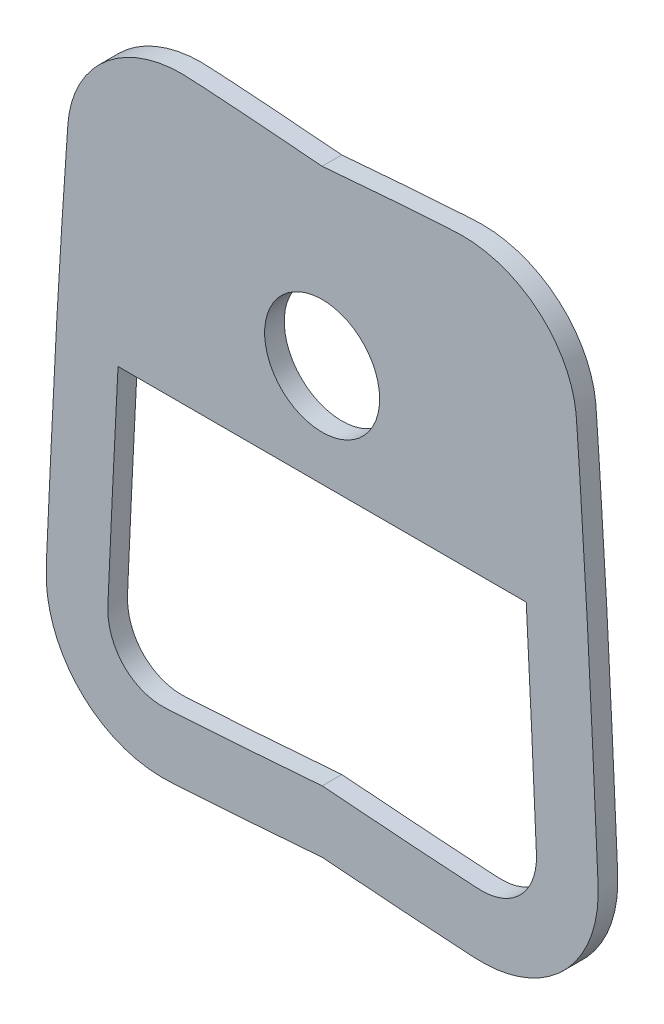
SolidWorks part; units mm, degrees
material "Фанера"
ref_plane "Front Plane" through (0, 0, 0) normal (0, 0, 1) x (1, 0, 0)
ref_plane "Top Plane" through (0, 0, 0) normal (0, 1, 0) x (1, 0, 0)
ref_plane "Right Plane" through (0, 0, 0) normal (1, 0, 0) x (0, 0, -1)
sketch "Эскиз2" plane through (0, 0, 0) normal (0, 0, 1) x (1, 0, 0)
  line L0 (0.0002, 142.4737) -> (0.0002, 32.0804) construction
  line L1 (-29.1091, 89.0073) -> (29.109, 89.0073)
  circle A1 centre (0, 103.6369) radius 4.3081 construction
  circle A2 centre (0, 103.6369) radius 8.2
  spline S2 degree 3 poles (0, 43.7392) (0.774, 43.6784) (2.3219, 43.5569) (5.4182, 43.3194) (9.2893, 43.031) (13.1618, 42.7628) (16.2603, 42.556) (18.2795, 42.4223) (19.829, 42.3235) (20.7864, 42.2641) (21.4427, 42.2247) (21.9494, 42.1945) (22.4153, 42.1814) (22.8397, 42.1798) (23.5161, 42.1932) (24.4211, 42.254) (25.9575, 42.4683) (27.8265, 42.9386) (29.9778, 43.8332) (31.9662, 45.0352) (33.7585, 46.5263) (35.2935, 48.2541) (36.5751, 50.2162) (37.5523, 52.3332) (38.105, 54.2013) (38.3902, 55.7262) (38.4987, 56.6607) (38.551, 57.4525) (38.5708, 58.0629) (38.5684, 58.6713) (38.5362, 59.4435) (38.4938, 60.3708) (38.425, 61.9202) (38.3386, 63.836) (38.1977, 66.9444) (38.0221, 70.7707) (37.7348, 76.9141) (37.3647, 84.5565) (36.9475, 92.2471) (36.583, 98.3866) (36.2979, 102.9638) (35.9998, 107.5529) (35.7664, 111.0027) (35.6046, 113.3302) (35.5424, 114.2245) (35.4966, 114.8654) (35.4694, 115.2725) (35.4118, 115.9083) (35.279, 116.8133) (35.0277, 117.9094) (34.5635, 119.3731) (33.7816, 121.0943) (32.5083, 123.0216) (30.9852, 124.6902) (29.1803, 126.1544) (27.5041, 127.1401) (25.3505, 128.0897) (23.409, 128.6293) (21.5202, 128.866) (20.353, 128.9311) (19.2879, 128.9227) (18.2137, 128.846) (17.2299, 128.7853) (16.3005, 128.7246) (15.3917, 128.6651) (14.5031, 128.6059) (13.1677, 128.5157) (11.3632, 128.3907) (9.078, 128.2256) (6.7985, 128.0531) (4.5827, 127.8775) (2.325, 127.6918) (0.8119, 127.5588) (0, 127.4874) knots 0 0 0 0 0.015767 0.031534 0.063068 0.094601 0.110368 0.126135 0.1357 0.141901 0.145616 0.149053 0.152208 0.155081 0.157671 0.165946 0.173483 0.189156 0.204936 0.220629 0.236165 0.252111 0.267386 0.2836 0.29929 0.306809 0.315089 0.318377 0.322921 0.32749 0.330729 0.338618 0.346341 0.362227 0.377566 0.409533 0.440017 0.50247 0.564923 0.596433 0.627377 0.65806 0.68983 0.697599 0.705443 0.708037 0.710647 0.713729 0.721 0.729205 0.736538 0.752162 0.767416 0.783272 0.797847 0.814472 0.822575 0.845629 0.855017 0.861206 0.869358 0.876627 0.883074 0.889378 0.895542 0.90157 0.907464 0.922725 0.938305 0.953995 0.969152 0.983448 1 1 1 1 construction
  spline S3 degree 3 poles (0, 127.4874) (-0.5484, 127.5359) (-1.5966, 127.6285) (-3.0967, 127.7551) (-4.7859, 127.8937) (-6.7383, 128.0484) (-9.7405, 128.276) (-12.7364, 128.4878) (-15.7405, 128.6886) (-17.4164, 128.7977) (-18.5445, 128.868) (-19.0935, 128.9048) (-19.6713, 128.9252) (-20.3714, 128.9252) (-21.3283, 128.8823) (-22.828, 128.7123) (-24.7405, 128.2795) (-27.1793, 127.3552) (-29.6475, 125.8824) (-31.8744, 123.83) (-33.4877, 121.6318) (-34.5579, 119.4542) (-35.0467, 117.8648) (-35.2691, 116.8043) (-35.3671, 116.2217) (-35.4408, 115.6222) (-35.489, 114.9922) (-35.5347, 114.3247) (-35.5881, 113.5686) (-35.73, 111.5277) (-35.9533, 108.2526) (-36.3451, 102.257) (-36.8092, 94.7185) (-37.2262, 87.1491) (-37.5342, 81.0394) (-37.7522, 76.5283) (-37.9656, 71.9894) (-38.1394, 68.2173) (-38.2787, 65.1601) (-38.363, 63.2949) (-38.43, 61.8051) (-38.4797, 60.6971) (-38.5314, 59.5351) (-38.5811, 58.4168) (-38.5535, 57.4313) (-38.4964, 56.6729) (-38.4026, 55.8505) (-38.2454, 54.9051) (-37.8731, 53.3446) (-37.2011, 51.4698) (-36.0559, 49.337) (-34.6245, 47.4301) (-32.8958, 45.7468) (-30.9374, 44.3573) (-28.7768, 43.2834) (-26.8641, 42.6757) (-25.2893, 42.3656) (-24.1298, 42.2273) (-22.9233, 42.1676) (-21.9573, 42.1912) (-21.168, 42.2417) (-20.6015, 42.2755) (-19.9623, 42.3153) (-19.0057, 42.3758) (-17.9649, 42.4432) (-16.7625, 42.5228) (-15.6619, 42.5959) (-14.1289, 42.6985) (-12.1179, 42.8348) (-8.905, 43.0601) (-5.6195, 43.3041) (-2.4082, 43.5501) (-0.8027, 43.6762) (0, 43.7392) knots 0 0 0 0 0.011181 0.021372 0.030575 0.045603 0.061149 0.091723 0.106599 0.122298 0.125831 0.129556 0.13347 0.137573 0.143772 0.152913 0.168196 0.183457 0.205727 0.226104 0.244563 0.260782 0.275163 0.278191 0.282787 0.287159 0.290453 0.295617 0.300749 0.305846 0.337168 0.36742 0.427874 0.490561 0.521384 0.552117 0.582286 0.613668 0.628808 0.644442 0.651588 0.659095 0.666967 0.675214 0.68182 0.686975 0.690658 0.698628 0.706421 0.72322 0.738904 0.755424 0.771444 0.787719 0.803991 0.820255 0.828308 0.836564 0.843949 0.852824 0.85617 0.860012 0.864349 0.869177 0.879481 0.88553 0.893651 0.901883 0.916735 0.934588 0.967294 0.983647 1 1 1 1 construction
  spline S4 degree 1 poles (0.0001, 51.7639) (-0.0019, 119.4564) knots 0 0 1 1 construction
  spline S5 degree 1 poles (-0.0019, 119.4564) (0.0001, 51.7639) knots 0 0 1 1 construction
  spline S6 degree 3 poles (0.0001, 51.7639) (1.5422, 51.6427) (4.6296, 51.401) (9.243, 51.0555) (13.08, 50.7868) (16.1635, 50.5801) (18.0968, 50.4516) (19.6289, 50.3523) (20.5869, 50.2918) (21.254, 50.2507) (21.6314, 50.2278) (21.9256, 50.2102) (22.1901, 50.1945) (22.3388, 50.1873) (22.487, 50.1828) (22.8167, 50.1783) (23.2689, 50.1916) (24.0642, 50.2695) (25.0003, 50.4673) (26.0799, 50.8663) (27.0688, 51.4124) (27.9574, 52.0949) (28.7407, 52.9108) (29.4014, 53.845) (29.9298, 54.8885) (30.2479, 55.8344) (30.4233, 56.6228) (30.5142, 57.2296) (30.556, 57.7405) (30.5692, 58.1757) (30.5687, 58.4382) (30.5634, 58.6211) (30.5529, 58.8728) (30.5404, 59.1612) (30.5151, 59.7274) (30.4574, 61.0064) (30.3716, 62.9287) (30.2659, 65.2578) (30.1601, 67.5799) (30.0176, 70.6778) (29.7646, 76.0976) (29.4758, 82.0809) (29.2034, 87.2793) (29.0352, 90.363) (28.8501, 93.6446) (28.6103, 97.6967) (28.3225, 102.3235) (28.0723, 106.1791) (27.8916, 108.8771) (27.7868, 110.4188) (27.7074, 111.5742) (27.6403, 112.5392) (27.5865, 113.3126) (27.5533, 113.7866) (27.5256, 114.1729) (27.4961, 114.6058) (27.4793, 114.8088) (27.4496, 115.0557) (27.3943, 115.392) (27.3, 115.8066) (27.0984, 116.4438) (26.7372, 117.2359) (26.1497, 118.1141) (25.1669, 119.176) (23.9141, 120.0231) (22.4672, 120.583) (21.4971, 120.8065) (20.6992, 120.9008) (20.201, 120.9255) (19.78, 120.9237) (19.4766, 120.9129) (19.0179, 120.8838) (18.163, 120.8267) (17.2431, 120.7699) (16.074, 120.6926) (14.9273, 120.6165) (13.3895, 120.5121) (11.4734, 120.3785) (8.414, 120.1552) (5.3428, 119.9155) (2.3164, 119.6612) (0.7679, 119.5241) (-0.0019, 119.4564) knots -0.004253 -0.004253 -0.004253 -0.004253 0.027279 0.058811 0.090343 0.106109 0.121875 0.129759 0.137642 0.141583 0.143554 0.145525 0.147495 0.149466 0.151437 0.153408 0.161291 0.169174 0.18494 0.200706 0.216472 0.232238 0.248004 0.26377 0.279536 0.295302 0.303185 0.311068 0.318951 0.322893 0.326834 0.328805 0.330776 0.332746 0.334717 0.3426 0.358366 0.374132 0.389898 0.405664 0.437196 0.500261 0.527717 0.543483 0.563325 0.594857 0.626389 0.657921 0.673687 0.68157 0.689453 0.697336 0.701278 0.705219 0.70719 0.709161 0.713102 0.717044 0.720985 0.728868 0.736751 0.752517 0.768283 0.784049 0.815582 0.831348 0.847114 0.854997 0.86288 0.866821 0.870763 0.874704 0.878646 0.886529 0.894412 0.902295 0.910178 0.925944 0.94171 0.973242 0.989008 1.004774 1.004774 1.004774 1.004774
  spline S7 degree 3 poles (-0.0019, 119.4564) (-0.7698, 119.5242) (-2.3118, 119.6615) (-5.3473, 119.9152) (-8.4132, 120.1552) (-11.4731, 120.3784) (-13.7726, 120.539) (-15.6942, 120.6678) (-17.0401, 120.7562) (-17.8067, 120.8057) (-18.3769, 120.842) (-18.8623, 120.8721) (-19.2727, 120.899) (-19.4779, 120.9114) (-19.6278, 120.9182) (-19.8368, 120.9244) (-20.1909, 120.9254) (-20.7023, 120.9009) (-21.4955, 120.8063) (-22.4658, 120.5842) (-23.9103, 120.0245) (-25.1675, 119.1756) (-26.1489, 118.1151) (-26.7389, 117.232) (-27.0968, 116.4493) (-27.3022, 115.7974) (-27.3928, 115.4011) (-27.4431, 115.0936) (-27.4659, 114.9214) (-27.4774, 114.8174) (-27.488, 114.6997) (-27.5127, 114.3681) (-27.5453, 113.898) (-27.5871, 113.3007) (-27.6405, 112.539) (-27.7074, 111.5717) (-27.7869, 110.416) (-27.8918, 108.8736) (-28.0726, 106.1765) (-28.3227, 102.3205) (-28.6106, 97.6944) (-28.8501, 93.6433) (-29.0352, 90.362) (-29.2036, 87.2786) (-29.4757, 82.081) (-29.7648, 76.0951) (-30.0177, 70.6763) (-30.1601, 67.5786) (-30.2662, 65.255) (-30.3538, 63.3188) (-30.4235, 61.7694) (-30.4758, 60.6068) (-30.5185, 59.6416) (-30.5539, 58.8626) (-30.5684, 58.4381) (-30.5695, 58.1742) (-30.56, 57.8625) (-30.5387, 57.5326) (-30.499, 57.1267) (-30.4233, 56.6232) (-30.2478, 55.8336) (-29.929, 54.8871) (-29.4012, 53.8441) (-28.7402, 52.9103) (-27.9574, 52.0948) (-27.0665, 51.4111) (-26.0801, 50.8662) (-24.9975, 50.467) (-24.0696, 50.2699) (-23.2587, 50.191) (-22.7849, 50.1771) (-22.324, 50.1876) (-21.9772, 50.2059) (-21.3268, 50.2467) (-20.5986, 50.2907) (-19.6237, 50.3527) (-18.0991, 50.4513) (-16.1627, 50.5802) (-13.0782, 50.7868) (-9.2439, 51.0555) (-4.6291, 51.401) (-1.542, 51.6428) (0.0001, 51.7639) knots -0.004774 -0.004774 -0.004774 -0.004774 0.010992 0.026758 0.05829 0.074056 0.089822 0.105588 0.113471 0.117413 0.121354 0.125296 0.127266 0.129237 0.131208 0.133179 0.13712 0.145003 0.152886 0.168652 0.184418 0.21595 0.231717 0.247483 0.263249 0.271132 0.279015 0.282956 0.284927 0.286898 0.288868 0.290839 0.294781 0.298722 0.302664 0.310547 0.31843 0.326313 0.342079 0.373611 0.405143 0.436675 0.456499 0.472265 0.499739 0.562804 0.594336 0.610102 0.625868 0.641634 0.649517 0.6574 0.665283 0.669224 0.673166 0.677107 0.681049 0.68499 0.688932 0.696815 0.704698 0.720464 0.73623 0.751996 0.767762 0.783528 0.799294 0.81506 0.830826 0.838709 0.846593 0.850534 0.854476 0.858417 0.862359 0.870242 0.878125 0.893891 0.909657 0.941189 0.972721 1.004253 1.004253 1.004253 1.004253
  spline S8 degree 1 poles (0, 42.9368) (0.0002, 128.2905) knots 0 0 1 1 construction
  spline S9 degree 1 poles (0.0002, 128.2905) (0, 42.9368) knots 0 0 1 1 construction
  spline S10 degree 3 poles (0, 42.9368) (3.067, 42.6959) (7.6671, 42.3407) (13.8079, 41.9178) (17.6422, 41.6576) (20.332, 41.4944) (21.8672, 41.3895) (23.4939, 41.3645) (25.4979, 41.5458) (28.6557, 42.2954) (32.3308, 44.0858) (35.9131, 47.4475) (38.3517, 51.6969) (39.2064, 55.2633) (39.3721, 57.6662) (39.3641, 59.2909) (39.2097, 61.9411) (39.0559, 65.8023) (38.8386, 70.4033) (38.6252, 75.0129) (38.4046, 79.6203) (38.0995, 85.7648) (37.6849, 93.4448) (37.2183, 101.1217) (36.8709, 106.4932) (36.6651, 109.5632) (36.5105, 111.8628) (36.3696, 113.7875) (36.2773, 115.308) (36.0967, 116.9449) (35.6112, 118.9138) (34.338, 121.9196) (31.8813, 125.2086) (28.5527, 127.5934) (25.5712, 128.8586) (23.2184, 129.4757) (20.8128, 129.7689) (18.3873, 129.674) (16.1209, 129.512) (13.0387, 129.3125) (9.2066, 129.0403) (4.6006, 128.6872) (1.5335, 128.4253) (0.0002, 128.2905) knots 0.000425 0.000425 0.000425 0.000425 0.062869 0.094091 0.125312 0.140923 0.148729 0.156534 0.172145 0.187756 0.218978 0.2502 0.281421 0.312643 0.320449 0.328254 0.343865 0.375087 0.406309 0.43753 0.468752 0.499974 0.562418 0.624861 0.656083 0.671694 0.687305 0.702916 0.710721 0.718526 0.734137 0.749748 0.78097 0.812192 0.827803 0.843414 0.859025 0.874635 0.890246 0.905857 0.937079 0.968301 0.999523 0.999523 0.999523 0.999523
  spline S11 degree 3 poles (0.0002, 128.2905) (-1.5331, 128.426) (-4.6005, 128.6868) (-9.206, 129.0405) (-13.039, 129.3121) (-16.1193, 129.5127) (-18.3903, 129.6721) (-20.8107, 129.7694) (-23.2183, 129.4755) (-25.5662, 128.8608) (-28.5502, 127.5948) (-31.8825, 125.2079) (-34.3394, 121.9177) (-35.6119, 118.911) (-36.0975, 116.9415) (-36.2768, 115.3042) (-36.3699, 113.7846) (-36.5106, 111.8597) (-36.6652, 109.5604) (-36.8712, 106.4903) (-37.2184, 101.1191) (-37.6849, 93.4424) (-38.0998, 85.7626) (-38.4045, 79.6184) (-38.6253, 75.0111) (-38.8388, 70.4018) (-39.0553, 65.8003) (-39.2117, 61.9414) (-39.3618, 59.2876) (-39.3729, 57.6638) (-39.2052, 55.2636) (-38.3518, 51.6961) (-35.9124, 47.4467) (-32.3305, 44.0856) (-28.653, 42.2946) (-25.499, 41.5461) (-23.4895, 41.3638) (-21.8711, 41.3905) (-20.3295, 41.4941) (-17.643, 41.6578) (-13.8072, 41.9178) (-7.6669, 42.3407) (-3.0669, 42.6959) (0, 42.9368) knots 0.000477 0.000477 0.000477 0.000477 0.031699 0.062921 0.094143 0.109754 0.125365 0.140975 0.156586 0.172197 0.187808 0.21903 0.250252 0.265863 0.281474 0.289279 0.297084 0.312695 0.328306 0.343917 0.375139 0.437582 0.500026 0.531248 0.56247 0.593691 0.624913 0.656135 0.671746 0.679551 0.687357 0.718579 0.7498 0.781022 0.812244 0.827855 0.843466 0.851271 0.859077 0.874688 0.905909 0.937131 0.999575 0.999575 0.999575 0.999575
  dimension "D3" = 16.4
  dimension "D1" = 8
  dimension "D2" = 0.8
extrude "Бобышка-Вытянуть2" add sketch "Эскиз2" along normal mid plane 2.8 contours S6 S7 L1 A2 | S10 S11 S7 S6
